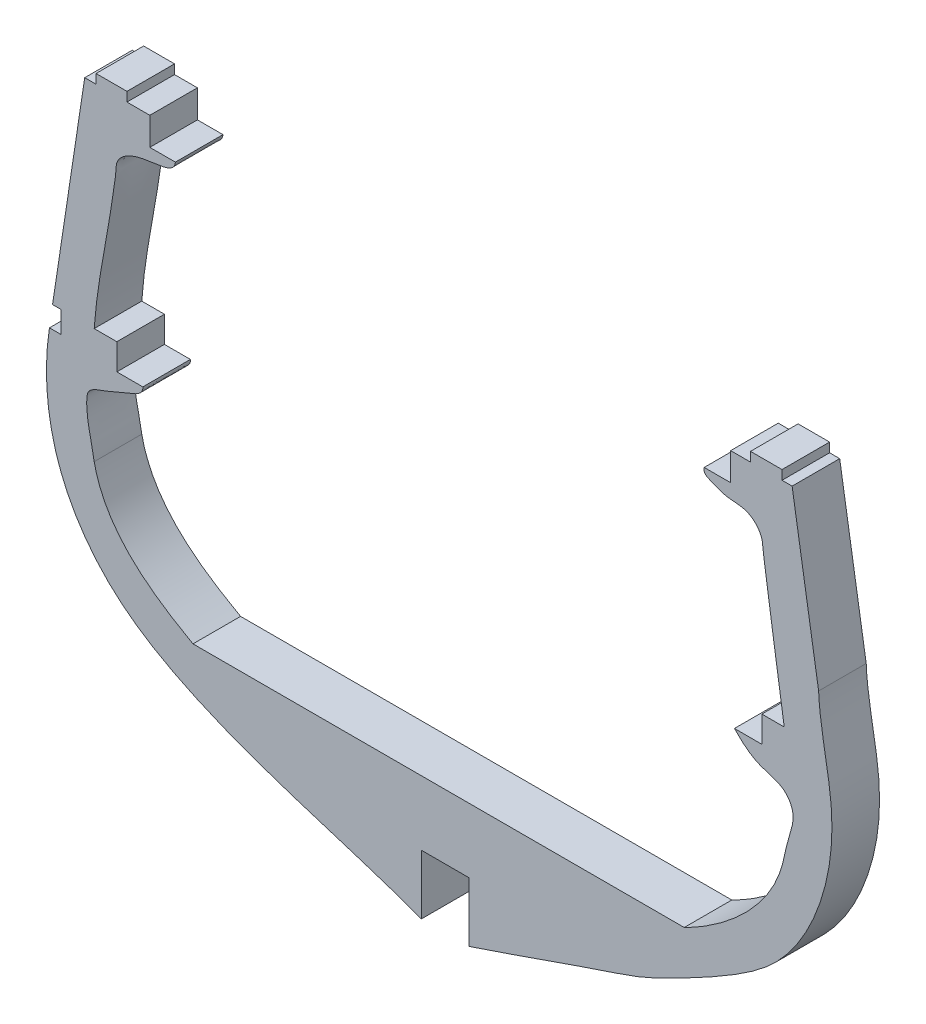
SolidWorks part; units mm, degrees
ref_plane "前视基准面" through (0, 0, 0) normal (0, 0, 1) x (1, 0, 0)
ref_plane "上视基准面" through (0, 0, 0) normal (0, 1, 0) x (1, 0, 0)
ref_plane "右视基准面" through (0, 0, 0) normal (1, 0, 0) x (0, 0, -1)
other "Configuration Table"
sketch "草图1" plane through (0, 0, 0) normal (0, 0, 1) x (1, 0, 0)
  line L0 (376.6667, 613.5) -> (1883.3333, 613.5) construction
  line L1 (2018.2839, -284.3484) -> (2018.2839, -294.3484)
  line L30 (2054.4576, -273.5049) -> (1971.8903, -273.5049)
  line L32 (2018.2839, -284.3484) -> (2010.2822, -284.3484)
  line L33 (2010.2822, -284.3484) -> (2010.2822, -294.3484)
  line L34 (2072.5914, -200.1901) -> (2070.8964, -200.1901)
  line L35 (2070.8964, -200.1901) -> (2070.8964, -198.6262)
  line L36 (2070.8964, -198.6262) -> (2065.5994, -198.6262)
  line L37 (2065.5994, -198.6262) -> (2065.5994, -200.1901)
  line L38 (2065.5994, -200.1901) -> (2062.2622, -200.1901)
  line L39 (2062.2622, -200.1901) -> (2062.2622, -204.8596)
  line L40 (2062.2622, -204.8596) -> (2057.8128, -204.8596)
  line L41 (2071.2672, -235.9171) -> (2067.5063, -235.9171)
  line L42 (2067.5063, -235.9171) -> (2067.5063, -240.3136)
  line L43 (2067.5063, -240.3136) -> (2062.8979, -240.3136)
  line L44 (1948.2861, -235.9171) -> (1949.7062, -235.9171)
  line L45 (1949.7062, -235.9171) -> (1949.7062, -239.5624)
  line L46 (1949.7062, -239.5624) -> (1947.7665, -239.5624)
  line L47 (1955.283, -235.9171) -> (1959.0932, -235.9171)
  line L48 (1959.0932, -235.9171) -> (1959.0932, -240.3136)
  line L49 (1959.0932, -240.3136) -> (1963.4577, -240.3136)
  line L50 (1953.6897, -200.1901) -> (1955.5948, -200.1901)
  line L51 (1955.5948, -200.1901) -> (1955.5948, -198.6262)
  line L52 (1955.5948, -198.6262) -> (1960.7905, -198.6262)
  line L53 (1960.7905, -198.6262) -> (1960.7905, -200.1901)
  line L54 (1960.7905, -200.1901) -> (1964.6354, -200.1901)
  line L55 (1964.6354, -200.1901) -> (1964.6354, -204.8596)
  line L56 (1964.6354, -204.8596) -> (1968.9306, -204.8596)
  spline S8 degree 3 poles (1968.9306, -204.8596) (1968.8249, -206.043) (1966.9622, -206.6337) (1964.2245, -206.9528) (1961.442, -207.4225) (1958.9295, -209.2287) (1958.9855, -211.1524) (1958.6271, -213.5907) (1957.4512, -221.8272) (1955.7139, -229.5994) (1955.283, -235.9171) knots 0 0 0 0 0.079837 0.134651 0.222997 0.305779 0.343473 0.36885 0.501792 1 1 1 1
  spline S9 degree 1 poles (1953.6897, -200.1901) (1948.2861, -235.9171) knots 0 0 1 1
  spline S10 degree 3 poles (1947.7665, -239.5624) (1946.6339, -246.7567) (1947.8164, -259.5684) (1958.1367, -273.331) (1978.5848, -285.4159) (1997.0186, -289.4007) (2010.2822, -294.3484) knots 0 0 0 0 0.237699 0.396499 0.538899 1 1 1 1
  spline S11 degree 3 poles (1971.8903, -273.5049) (1964.6261, -269.4785) (1957.1194, -264.141) (1955.283, -255.2866) knots 0 0 0 0 1 1 1 1
  spline S12 degree 3 poles (1963.4577, -240.3136) (1963.5291, -241.1212) (1962.2395, -242.0615) (1959.7162, -242.8699) (1957.232, -244.1601) (1954.1228, -245.0333) (1953.8515, -249.6307) (1954.8052, -252.2364) (1955.283, -255.2866) knots 0 0 0 0 0.102963 0.208523 0.386782 0.529425 0.602819 1 1 1 1
  spline S13 degree 1 poles (2072.5914, -200.1901) (2077.0474, -227.778) knots 0 0 1 1
  spline S14 degree 3 poles (2077.0474, -227.778) (2077.2612, -233.2756) (2079.7848, -241.8106) (2078.7853, -256.8752) (2073.0051, -269.175) (2062.1744, -276.9203) (2045.4817, -285.5035) (2046.3686, -284.5014) (2021.2519, -293.4148) (2018.2839, -294.3484) knots 0 0 0 0 0.157382 0.247757 0.428753 0.514164 0.636987 0.881281 0.970187 0.970187 0.970187 0.970187
  spline S15 degree 3 poles (2057.8128, -204.8596) (2057.5474, -205.7471) (2059.3801, -206.4452) (2061.7759, -207.4565) (2065.2179, -207.162) (2067.5736, -209.6734) (2067.6976, -211.9655) (2068.9502, -220.455) (2070.1077, -228.4904) (2071.2672, -235.9171) knots 0 0 0 0 0.060524 0.124111 0.219635 0.316289 0.355323 0.400899 1 1 1 1
  spline S16 degree 3 poles (2054.4576, -273.5049) (2061.3382, -270.1025) (2070.0278, -262.8683) (2071.7393, -251.9993) (2073.4186, -248.002) (2070.9603, -244.3048) (2066.6026, -243.8215) (2064.0884, -241.5655) (2062.8979, -240.3136) knots 0 0 0 0 0.528587 0.619056 0.732797 0.785422 0.885179 1 1 1 1
  dimension "D1" = 8.0018
  dimension "D2" = 10
  dimension "D3" = 130.5397
extrude "凸台-拉伸1" add sketch "草图1" along normal blind 8
